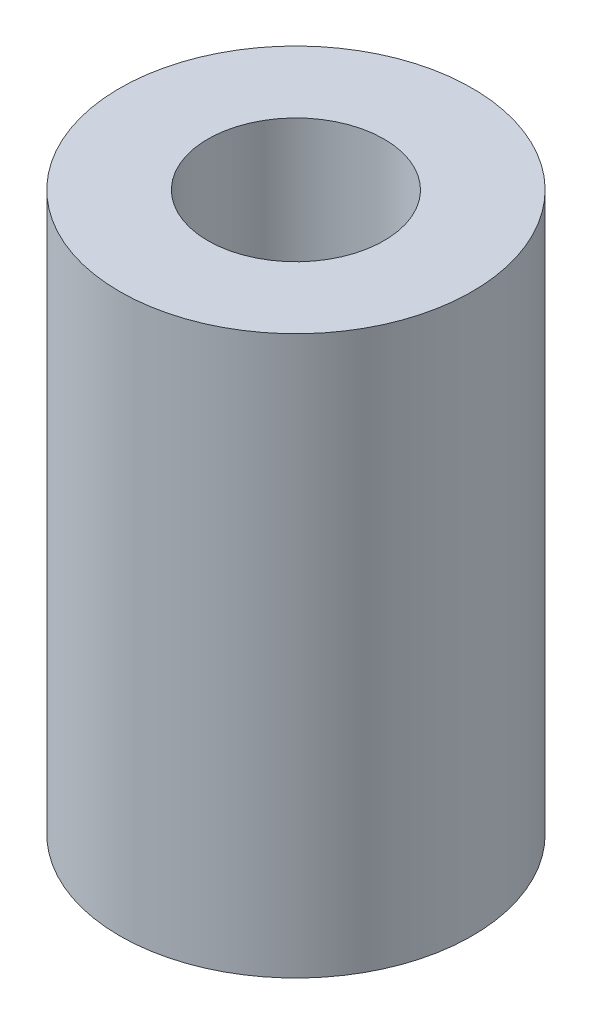
SolidWorks part; units mm, degrees
ref_plane "Front Plane" through (0, 0, 0) normal (0, 0, 1) x (1, 0, 0)
ref_plane "Top Plane" through (0, 0, 0) normal (0, 1, 0) x (1, 0, 0)
ref_plane "Right Plane" through (0, 0, 0) normal (1, 0, 0) x (0, 0, -1)
sketch "Sketch1" plane through (0, 0, 0) normal (0, 1, 0) x (1, 0, 0)
  circle A0 centre (0, 0) radius 3
  circle A1 centre (0, 0) radius 6
  dimension "D1" = 6
  dimension "D2" = 12
extrude "Boss-Extrude1" add sketch "Sketch1" along normal blind 19 contours A1 | A0
